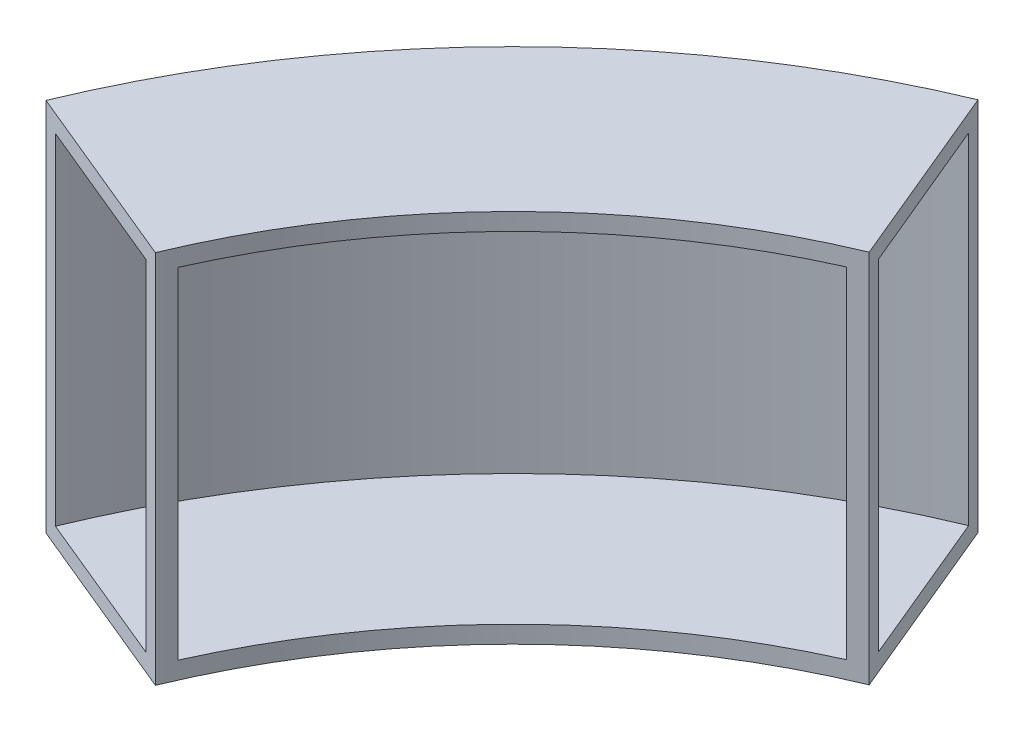
SolidWorks part; units mm, degrees
material "Alumina"
ref_plane "Front Plane" through (0, 0, 0) normal (0, 0, 1) x (1, 0, 0)
ref_plane "Top Plane" through (0, 0, 0) normal (0, 1, 0) x (1, 0, 0)
ref_plane "Right Plane" through (0, 0, 0) normal (1, 0, 0) x (0, 0, -1)
sketch "Sketch1" plane through (0, 0, 0) normal (0, 1, 0) x (1, 0, 0)
  line L0 (0, 1495.54) -> (0, -1495.54) construction
  line L1 (0, 0) -> (1057.5065, 1057.5065) construction
  line L2 (1057.5065, 1057.5065) -> (-1057.5065, -1057.5065) construction
  line L3 (-1057.5065, -1057.5065) -> (1057.5065, -1057.5065) construction
  line L4 (1057.5065, -1057.5065) -> (-1057.5065, 1057.5065) construction
  line L5 (-1057.5065, 1057.5065) -> (1057.5065, 1057.5065) construction
  line L6 (440.104, -1057.5065) -> (574.625, -1380.7411)
  line L7 (440.104, 1057.5065) -> (574.625, 1380.7411)
  line L8 (-440.104, 1057.5065) -> (-574.625, 1380.7411)
  line L9 (-440.104, -1057.5065) -> (-574.625, -1380.7411)
  line L10 (-1058.4838, 437.7482) -> (-1382.0172, 571.5491)
  circle A0 centre (0, 0) radius 1495.54
  arc A2 (440.104, 1057.5065) -> (440.104, -1057.5065) centre (0, 0) cw
  arc A3 (-440.104, -1057.5065) -> (-440.104, 1057.5065) centre (0, 0) cw
  arc A4 (-440.104, 1057.5065) -> (-1058.4838, 437.7482) centre (0, 0) ccw
extrude "Boss-Extrude1" add sketch "Sketch1" along normal blind 650 contours L10 A3 L8 A0
sketch "Sketch3" plane through (0, 0, 0) normal (-0.3822, 0, 0.9241) x (0.9241, 0, 0.3822)
  line L0 (-1145.4307, 0) -> (-1495.54, 650) construction
  line L1 (-1495.54, 0) -> (-1145.4307, 650) construction
  line L2 (-1145.4307, 650) -> (-1175.4307, 650) construction
  line L3 (-1145.4307, 650) -> (-1495.54, 650) construction
  line L4 (-1320.4853, 325) -> (-1320.4853, 650) construction
  line L5 (-1320.4853, 650) -> (-1320.4853, 0) construction
  line L6 (-1145.4307, 0) -> (-1495.54, 0) construction
  line L7 (-1495.54, 325) -> (-1145.4307, 325) construction
  line L8 (-1495.54, 650) -> (-1495.54, 0) construction
  line L9 (-1145.4307, 650) -> (-1145.4307, 0) construction
  line L10 (-1145.4307, 650) -> (-1145.4307, 620) construction
  line L11 (-1175.4307, 650) -> (-1175.4307, 620) construction
  line L12 (-1175.4307, 620) -> (-1145.4307, 620) construction
  line L13 (-1175.4307, 30) -> (-1145.4307, 30) construction
  line L14 (-1175.4307, 0) -> (-1175.4307, 30) construction
  line L15 (-1465.54, 620) -> (-1495.54, 620) construction
  line L16 (-1465.54, 30) -> (-1495.54, 30) construction
  line L17 (-1465.54, 0) -> (-1465.54, 30) construction
  line L18 (-1465.54, 650) -> (-1465.54, 620) construction
  line L19 (-1465.54, 620) -> (-1175.4307, 620)
  line L20 (-1175.4307, 620) -> (-1175.4307, 30)
  line L21 (-1175.4307, 30) -> (-1465.54, 30)
  line L22 (-1465.54, 30) -> (-1465.54, 620)
  line L23 (0, 0) -> (0, 1000.043) construction
revolve "Cut-Revolve1" cut sketch "Sketch3" angle 360 about L23
sketch "Sketch4" plane through (0, 0, 0) normal (-0.3822, 0, 0.9241) x (0.9241, 0, 0.3822)
  line L0 (-1175.4307, 620) -> (-1145.4307, 620)
  line L1 (-1145.4307, 650) -> (-1145.4307, 0) construction
  line L2 (-1175.4307, 30) -> (-1145.4307, 30)
  line L3 (-1145.4307, 30) -> (-1145.4307, 620)
  line L4 (-1175.4307, 620) -> (-1175.4307, 30)
  line L5 (0, 0) -> (0, 1002.6948) construction
revolve "Cut-Revolve2" cut sketch "Sketch4" about L5
sketch "Sketch5" plane through (0, 0, 0) normal (-0.3822, 0, 0.9241) x (0.9241, 0, 0.3822)
  line L2 (-1145.4307, 0) -> (-1495.54, 0) construction
  line L3 (0, 0) -> (0, 650) construction
  line L4 (-1145.4307, 650) -> (-1495.54, 650) construction
  line L6 (0, 0) -> (0, 587.3873) construction
  line L7 (-1145.4307, 620) -> (-1175.4307, 620)
  line L8 (-1145.4307, 620) -> (-1465.54, 620) construction
  line L9 (-1175.4307, 620) -> (-1175.4307, 30)
  line L10 (-1465.54, 30) -> (-1145.4307, 30) construction
  line L11 (-1175.4307, 30) -> (-1145.4307, 30)
  line L12 (-1145.4307, 30) -> (-1145.4307, 620)
sketch "Sketch7" plane through (0, 0, 0) normal (-0.3822, 0, 0.9241) x (0.9241, 0, 0.3822)
  line L0 (-1145.4307, 620) -> (-1145.4307, 30)
  line L1 (-1145.4307, 30) -> (-1175.4307, 30)
  line L2 (-1175.4307, 30) -> (-1175.4307, 620)
  line L3 (-1175.4307, 620) -> (-1145.4307, 620)
  line L4 (0, 0) -> (0, 650) construction
revolve "Revolve1" add sketch "Sketch7" angle 1.5 about L4
sketch "Sketch8" plane through (0, 0, 0) normal (0.9232, 0, -0.3842) x (-0.3842, 0, -0.9232)
  line L0 (1175.4307, 620) -> (1145.4307, 620)
  line L1 (1145.4307, 650) -> (1145.4307, 0) construction
  line L2 (1175.4307, 620) -> (1175.4307, 30)
  line L3 (1175.4307, 30) -> (1145.4307, 30)
  line L4 (1145.4307, 30) -> (1145.4307, 620)
  line L5 (0, 0) -> (0, 839.8381) construction
revolve "Cut-Revolve5" cut sketch "Sketch8" angle 2 about L5
sketch "Sketch9" plane through (0, 0, 0) normal (0.9232, 0, -0.3842) x (-0.3842, 0, -0.9232)
  line L7 (1145.4307, 620) -> (1175.4307, 620)
  line L8 (1145.4307, 620) -> (1465.54, 620) construction
  line L9 (1175.4307, 620) -> (1175.4307, 30)
  line L10 (1465.54, 30) -> (1145.4307, 30) construction
  line L11 (1175.4307, 30) -> (1145.4307, 30)
  line L12 (1145.4307, 30) -> (1145.4307, 620)
  line L13 (0, 0) -> (0, 807.4983) construction
revolve "Revolve2" add sketch "Sketch9" angle 1.5 about L13
